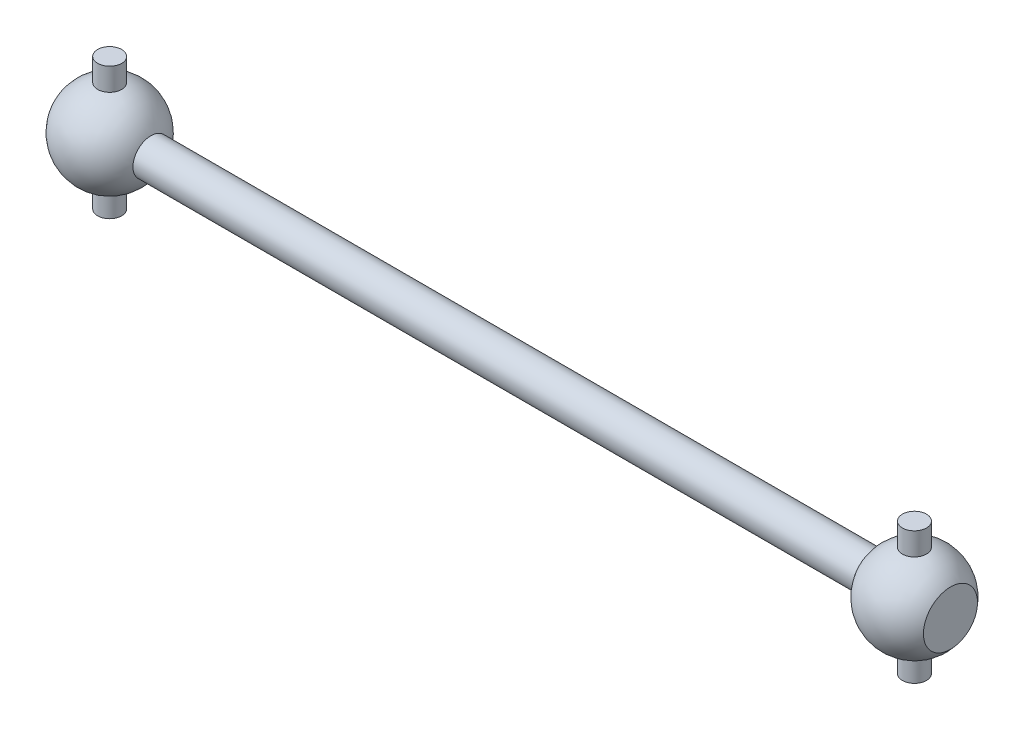
SolidWorks part; units mm, degrees
material "7050-T73510"
ref_plane "前视基准面" through (0, 0, 0) normal (0, 0, 1) x (1, 0, 0)
ref_plane "上视基准面" through (0, 0, 0) normal (0, 1, 0) x (1, 0, 0)
ref_plane "右视基准面" through (0, 0, 0) normal (1, 0, 0) x (0, 0, -1)
sketch "草图1" plane through (0, 0, 0) normal (0, 0, 1) x (1, 0, 0)
  line L0 (-104.6625, 0) -> (104.6625, 0) construction
  line L1 (73, 0) -> (73, 4.5)
  line L2 (60.1261, 3) -> (-60.1261, 3)
  line L3 (60.1261, -3) -> (-60.1261, -3)
  line L4 (0, 0) -> (0, 22.3771) construction
  line L5 (-73, 0) -> (-73, 4.5)
  line L6 (73, 0) -> (73, -4.5)
  line L7 (-73, 0) -> (-73, -4.5)
  line L8 (-73, 0) -> (73, 0)
  arc A0 (60.1261, -3) -> (73, -4.5) centre (67, 0) ccw
  arc A1 (-73, 4.5) -> (-60.1261, 3) centre (-67, 0) cw
  arc A2 (73, 4.5) -> (60.1261, 3) centre (67, 0) ccw
  arc A3 (-60.1261, -3) -> (-73, -4.5) centre (-67, 0) cw
  point P4 (0, 0)
  point P20 (0, 3)
  point P21 (0, -3)
  dimension "D1" = 15
  dimension "D2" = 73
  dimension "D3" = 3
  dimension "D4" = 9
revolve "旋转1" add sketch "草图1" angle 360 about L0
sketch "草图2" plane through (0, 0, 0) normal (0, 1, 0) x (1, 0, 0)
  circle A0 centre (67, 0) radius 2
  arc A1 (60.1261, -3) -> (73, -4.5) centre (67, 0) ccw construction
  dimension "D1" = 4
extrude "凸台-拉伸1" add sketch "草图2" along normal mid plane 22
mirror "镜向1" about plane through (0, 0, 0) normal (1, 0, 0) of "凸台-拉伸1"
